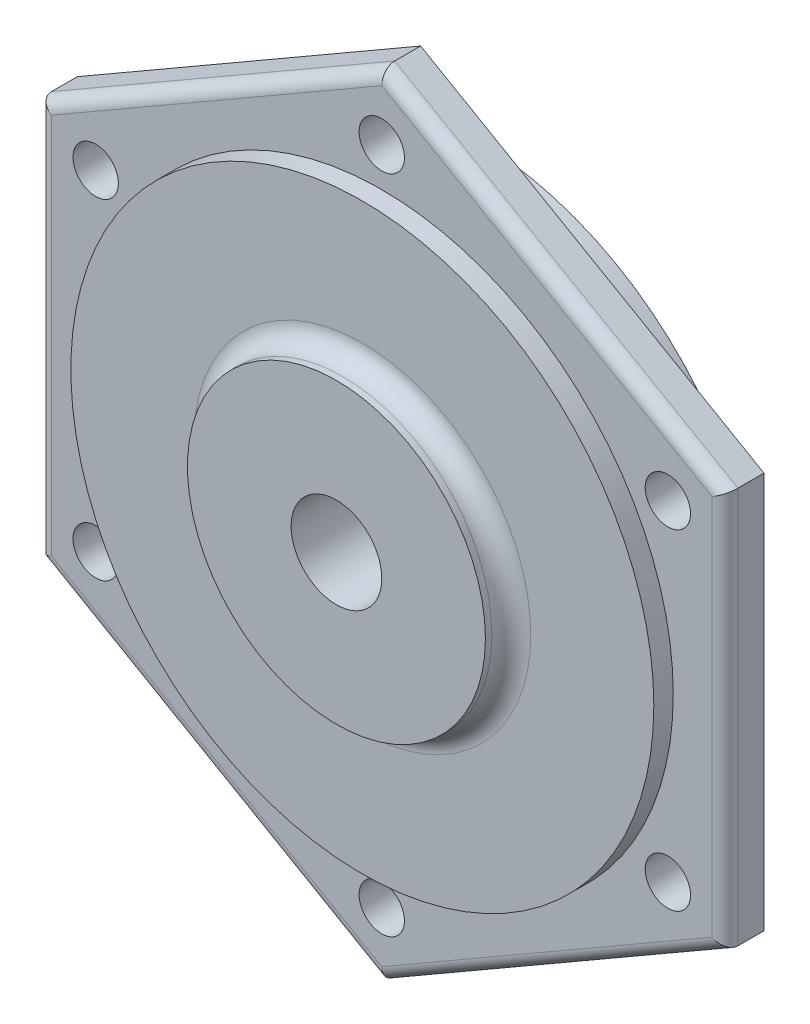
SolidWorks part; units mm, degrees
ref_plane "Front Plane" through (0, 0, 0) normal (0, 0, 1) x (1, 0, 0)
ref_plane "Top Plane" through (0, 0, 0) normal (0, 1, 0) x (1, 0, 0)
ref_plane "Right Plane" through (0, 0, 0) normal (1, 0, 0) x (0, 0, -1)
sketch "Sketch1" plane through (0, 0, 0) normal (1, 0, 0) x (0, 0, -1)
  line L1 (-3, 45) -> (-3, 26)
  line L2 (-6, 23) -> (-7, 23)
  line L3 (-7, 23) -> (-7, 7)
  line L4 (-7, 7) -> (0, 7)
  line L5 (0, 7) -> (0, 19)
  line L6 (0, 19) -> (8, 19)
  line L8 (3, 45) -> (-3, 45)
  line L9 (3, 45) -> (14, 45)
  line L10 (14, 45) -> (14, 40)
  line L11 (14, 40) -> (8, 40)
  line L12 (8, 40) -> (8, 19)
  line L13 (-21.0632, 0) -> (24.6475, 0) construction
  arc A0 (-3, 26) -> (-6, 23) centre (-6, 26) cw
  point P0 (-6.5, 23)
  point P5 (8, 29.5)
  point P11 (0, 45)
  dimension "D10" = 3
  dimension "D1" = 7
  dimension "D2" = 23
  dimension "D3" = 45
  dimension "D4" = 6
  dimension "D5" = 6
  dimension "D6" = 5
  dimension "D7" = 8
  dimension "D8" = 4
  dimension "D9" = 19
revolve "Revolve1" add sketch "Sketch1" angle 360 about L13
sketch "Sketch2" plane through (0, 0, 0) normal (0, 0, 1) x (1, 0, 0)
  line L1 (0, 61.1991) -> (-53, 30.5996)
  line L2 (-53, 30.5996) -> (-53, -30.5996)
  line L3 (-53, -30.5996) -> (0, -61.1991)
  line L4 (0, -61.1991) -> (53, -30.5996)
  line L5 (53, -30.5996) -> (53, 30.5996)
  line L6 (53, 30.5996) -> (0, 61.1991)
  circle A0 centre (0, 0) radius 53 construction
  dimension "D1" = 106
extrude "Boss-Extrude1" add sketch "Sketch2" against normal blind 6
sketch "Sketch3" plane through (0, 0, 0) normal (0, 0, 1) x (1, 0, 0)
  circle A0 centre (0, 51) radius 3.5
  circle A1 centre (44.1673, 25.5) radius 3.5
  circle A2 centre (44.1673, -25.5) radius 3.5
  circle A3 centre (0, -51) radius 3.5
  circle A4 centre (-44.1673, -25.5) radius 3.5
  circle A5 centre (-44.1673, 25.5) radius 3.5
  circle A6 centre (0, 0) radius 7 construction
  circle A7 centre (0, 0) radius 7
  point P15 (0, 0)
  dimension "D1" = 7
  dimension "D2" = 51
  dimension "D3" = 6
extrude "Cut-Extrude1" cut sketch "Sketch3" against normal through all
fillet "Fillet1" radius 2 6 edges at (-26.5, 45.8993, 0) (-53, 0, 0) (-26.5, -45.8993, 0) (26.5, -45.8993, 0) (53, 0, 0) (26.5, 45.8993, 0)
